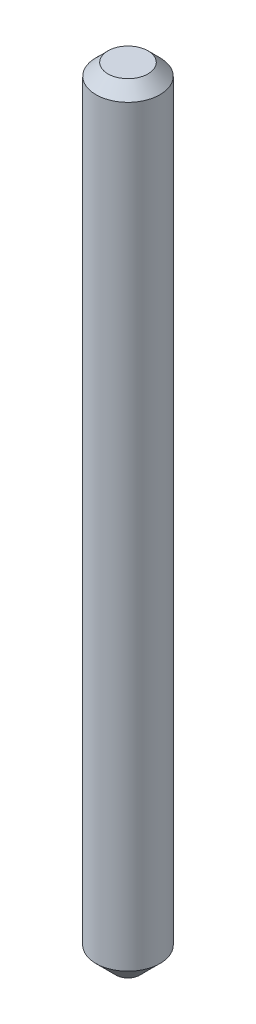
SolidWorks part; units mm, degrees
material "Cast Stainless Steel"
ref_plane "Front Plane" through (0, 0, 0) normal (0, 0, 1) x (1, 0, 0)
ref_plane "Top Plane" through (0, 0, 0) normal (0, 1, 0) x (1, 0, 0)
ref_plane "Right Plane" through (0, 0, 0) normal (1, 0, 0) x (0, 0, -1)
sketch "Sketch1" plane through (0, 0, 0) normal (0, 1, 0) x (1, 0, 0)
  circle A0 centre (0, 0) radius 4
  dimension "D1" = 8
extrude "Boss-Extrude1" add sketch "Sketch1" along normal blind 98
chamfer "Chamfer1" distance 2.5 angle 45 1 edges at (0, 0, 4)
chamfer "Chamfer2" distance 1.5 angle 45 1 edges at (0, 98, 4)
